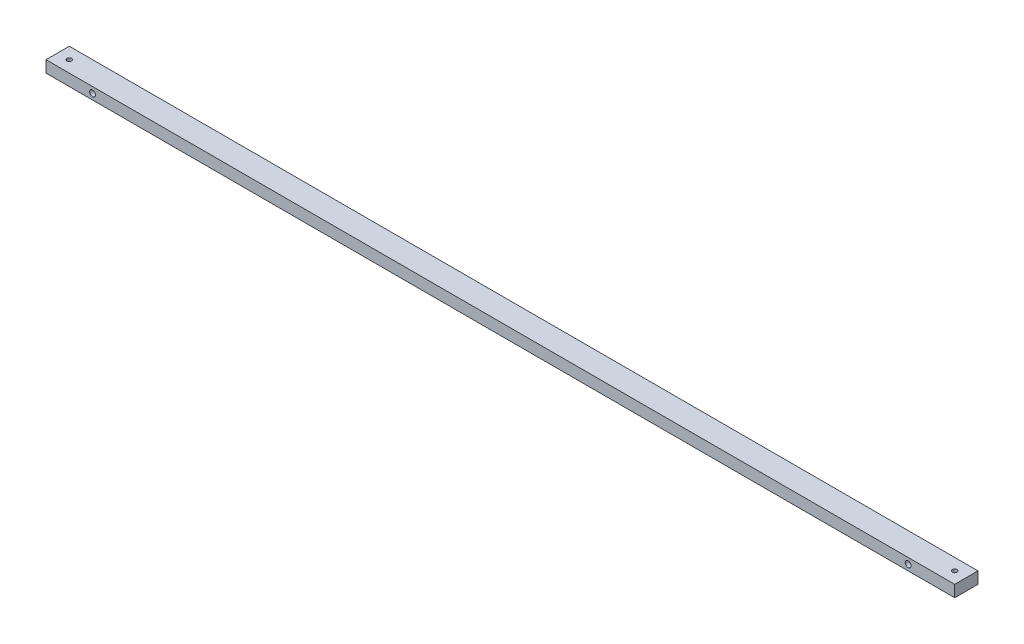
SolidWorks part; units mm, degrees
material "6061 Alloy"
ref_plane "Front Plane" through (0, 0, 0) normal (0, 0, 1) x (1, 0, 0)
ref_plane "Top Plane" through (0, 0, 0) normal (0, 1, 0) x (1, 0, 0)
ref_plane "Right Plane" through (0, 0, 0) normal (1, 0, 0) x (0, 0, -1)
sketch "Sketch1" plane through (0, 0, 0) normal (1, 0, 0) x (0, 0, -1)
  line L1 (0, 0) -> (25.4, 0)
  line L2 (0, 0) -> (0, 12.7)
  line L3 (0, 12.7) -> (25.4, 12.7)
  line L4 (25.4, 0) -> (25.4, 12.7)
  dimension "D1" = 25.4
  dimension "D2" = 12.7
extrude "Boss-Extrude1" add sketch "Sketch1" along normal blind 990.6
hole_wizard "1/4-20 Tapped Hole1" positions "Sketch2" profile "Sketch3" tap size "1/4-20" standard "ANSI Inch" end condition through all
sketch "Sketch2" plane through (0, 12.7, 0) normal (0, 1, 0) x (1, 0, 0)
  line L0 (0, 25.4) -> (0, 0) construction
  line L1 (990.6, 25.4) -> (0, 25.4) construction
  line L2 (990.6, 25.4) -> (990.6, 0) construction
  point P0 (12.7, 12.7)
  point P4 (977.9, 12.7)
  dimension "D1" = 12.7
  dimension "D2" = 12.7
  dimension "D3" = 12.7
  dimension "D4" = 12.7
sketch "Sketch3" plane through (12.7, 12.7, -12.7) normal (1, 0, 0) x (0, 0, 1)
  line L0 (0, 0) -> (0, 12.7)
  line L1 (0, 12.7) -> (2.5527, 12.7)
  line L2 (2.5527, 12.7) -> (2.5527, 0)
  line L5 (2.5527, 0) -> (0, 0)
  line L11 (0, -6.35) -> (0, 107.95) construction
  dimension "Thru Tap Drill Dia." = 5.1054
  dimension "Thru Tap Drill Depth" = 12.7
hole_wizard "1/4 (0.25) Diameter Hole1" positions "Sketch4" profile "Sketch6" hole size "1/4" standard "ANSI Inch" end condition through all
sketch "Sketch4" plane through (0, 0, -25.4) normal (0, 0, -1) x (-1, 0, 0)
  line L0 (-990.6, 0) -> (-990.6, 12.7) construction
  line L1 (-990.6, 0) -> (0, 0) construction
  line L2 (-990.6, 12.7) -> (0, 12.7) construction
  line L3 (0, 0) -> (0, 12.7) construction
  point P0 (-939.8, 6.35)
  point P2 (-50.8, 6.35)
  dimension "D1" = 50.8
  dimension "D2" = 6.35
  dimension "D3" = 6.35
  dimension "D4" = 50.8
sketch "Sketch6" plane through (939.8, 6.35, -25.4) normal (1, 0, 0) x (0, 1, 0)
  line L0 (0, 0) -> (0, 25.4)
  line L1 (0, 25.4) -> (3.175, 25.4)
  line L2 (3.175, 25.4) -> (3.175, 0)
  line L5 (3.175, 0) -> (0, 0)
  line L11 (0, -6.35) -> (0, 107.95) construction
  dimension "Thru Hole Dia." = 6.35
  dimension "Thru Hole Depth" = 25.4
